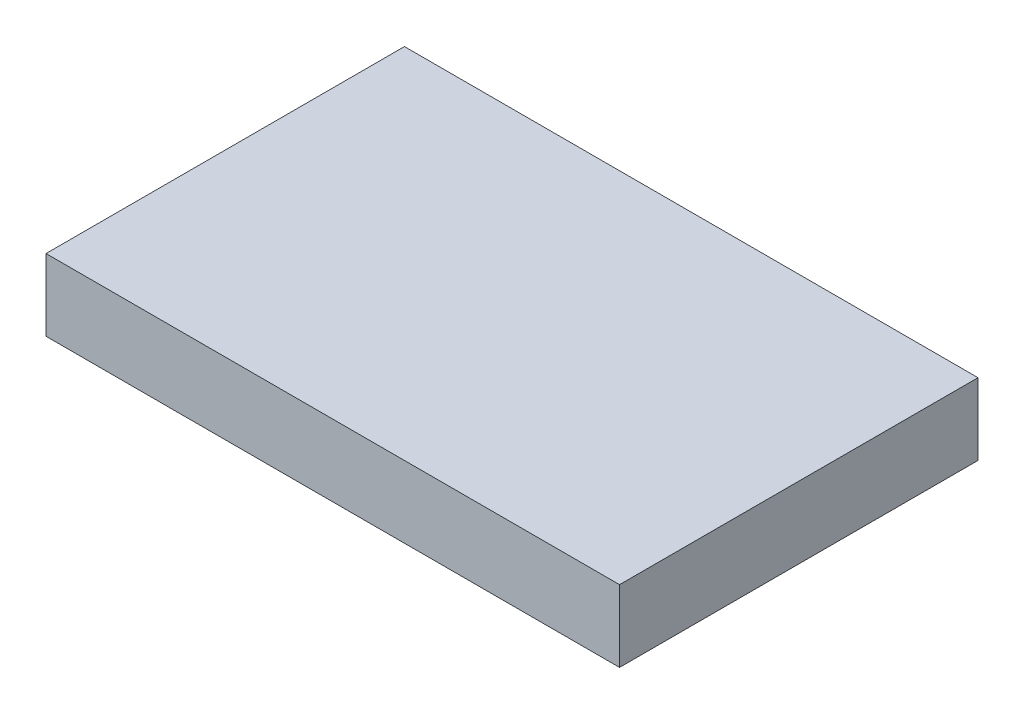
SolidWorks part; units mm, degrees
ref_plane "Front Plane" through (0, 0, 0) normal (0, 0, 1) x (1, 0, 0)
ref_plane "Top Plane" through (0, 0, 0) normal (0, 1, 0) x (1, 0, 0)
ref_plane "Right Plane" through (0, 0, 0) normal (1, 0, 0) x (0, 0, -1)
sketch "Sketch2" plane through (0, 0, 0) normal (0, 1, 0) x (1, 0, 0)
  line L1 (0, 0) -> (40, 0)
  line L2 (0, 0) -> (0, 25)
  line L3 (0, 25) -> (40, 25)
  line L4 (40, 0) -> (40, 25)
  point P5 (0, 0)
  point P6 (329.3081, 225.5081)
  point P7 (352.8078, 255.3531)
  point P8 (400.526, 327.5275)
extrude "Boss-Extrude1" add sketch "Sketch2" along normal blind 5 contours L2 L3 L4 L1
